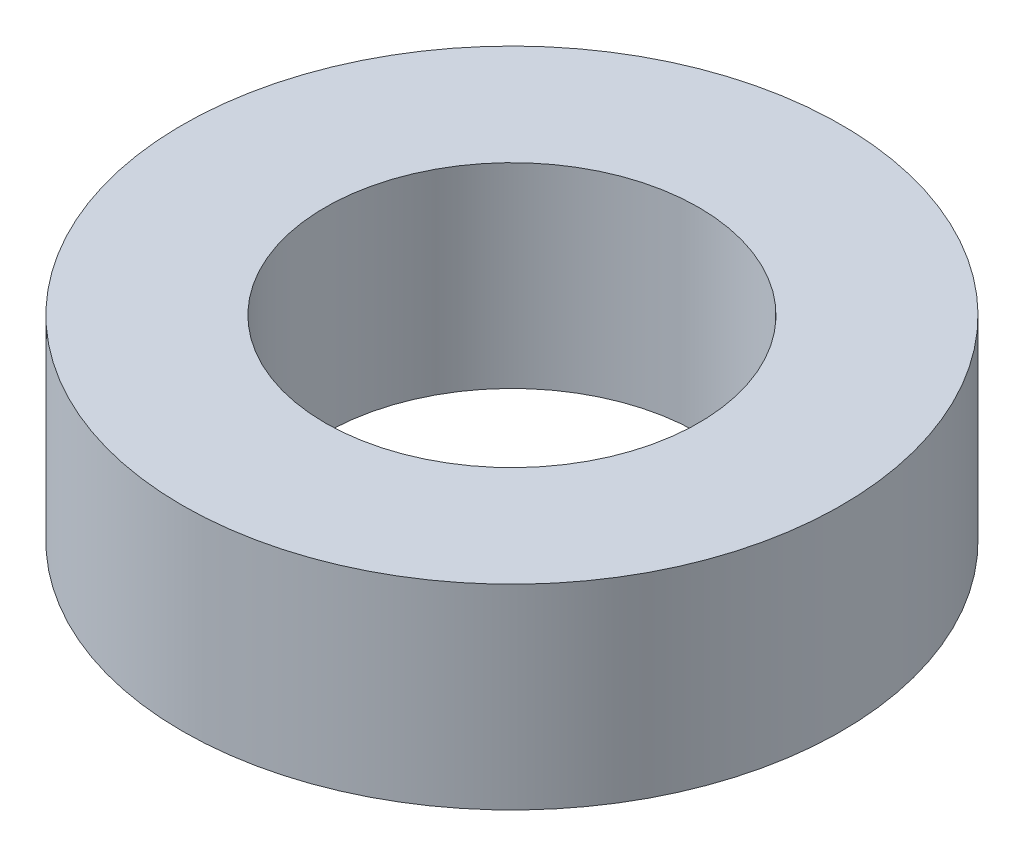
SolidWorks part; units mm, degrees
ref_plane "Спереди" through (0, 0, 0) normal (0, 0, 1) x (1, 0, 0)
ref_plane "Сверху" through (0, 0, 0) normal (0, 1, 0) x (1, 0, 0)
ref_plane "Справа" through (0, 0, 0) normal (1, 0, 0) x (0, 0, -1)
sketch "Эскиз2" plane through (0, 0, 0) normal (0, 1, 0) x (1, 0, 0)
  circle A0 centre (0, 0) radius 15
  circle A1 centre (0, 0) radius 8.5
extrude "Вытянуть1" add sketch "Эскиз2" along normal blind 8.9
